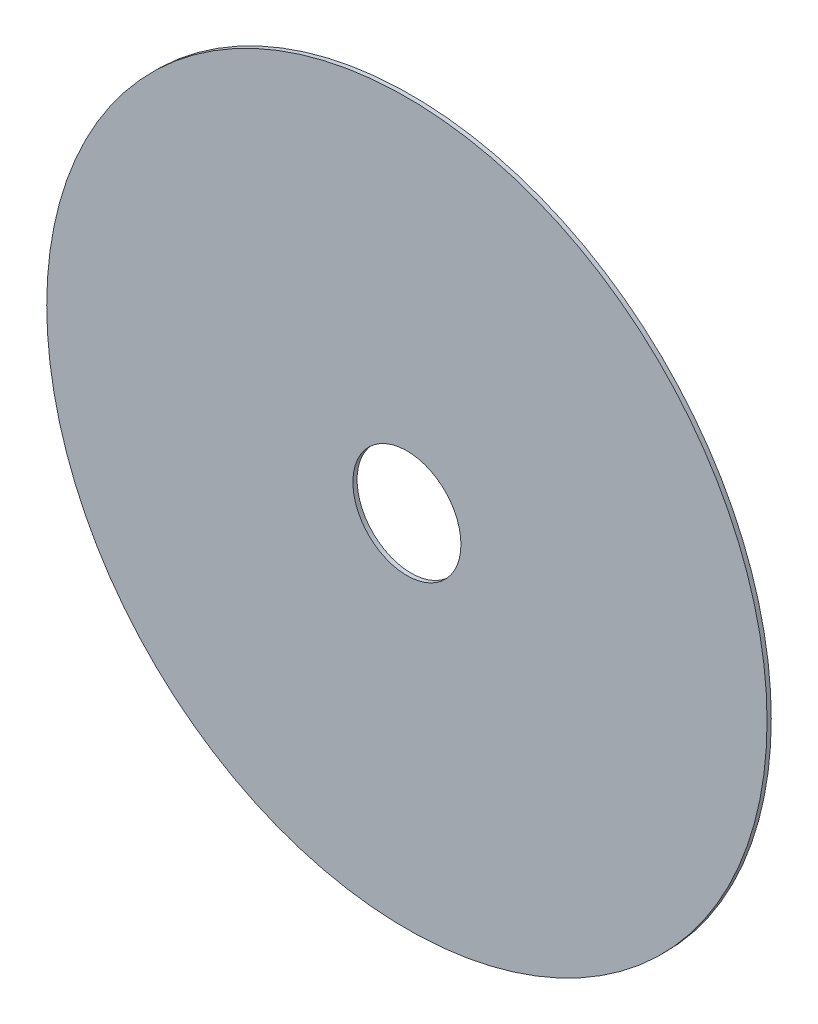
SolidWorks part; units mm, degrees
ref_plane "Front Plane" through (0, 0, 0) normal (0, 0, 1) x (1, 0, 0)
ref_plane "Top Plane" through (0, 0, 0) normal (0, 1, 0) x (1, 0, 0)
ref_plane "Right Plane" through (0, 0, 0) normal (1, 0, 0) x (0, 0, -1)
sketch "Sketch1" plane through (0, 0, 0) normal (0, 0, 1) x (1, 0, 0)
  circle A0 centre (0, 0) radius 2.286
  circle A1 centre (0, 0) radius 15.24
  dimension "D1" = 4.572
  dimension "D2" = 30.48
extrude "Boss-Extrude1" add sketch "Sketch1" along normal blind 0.1778
